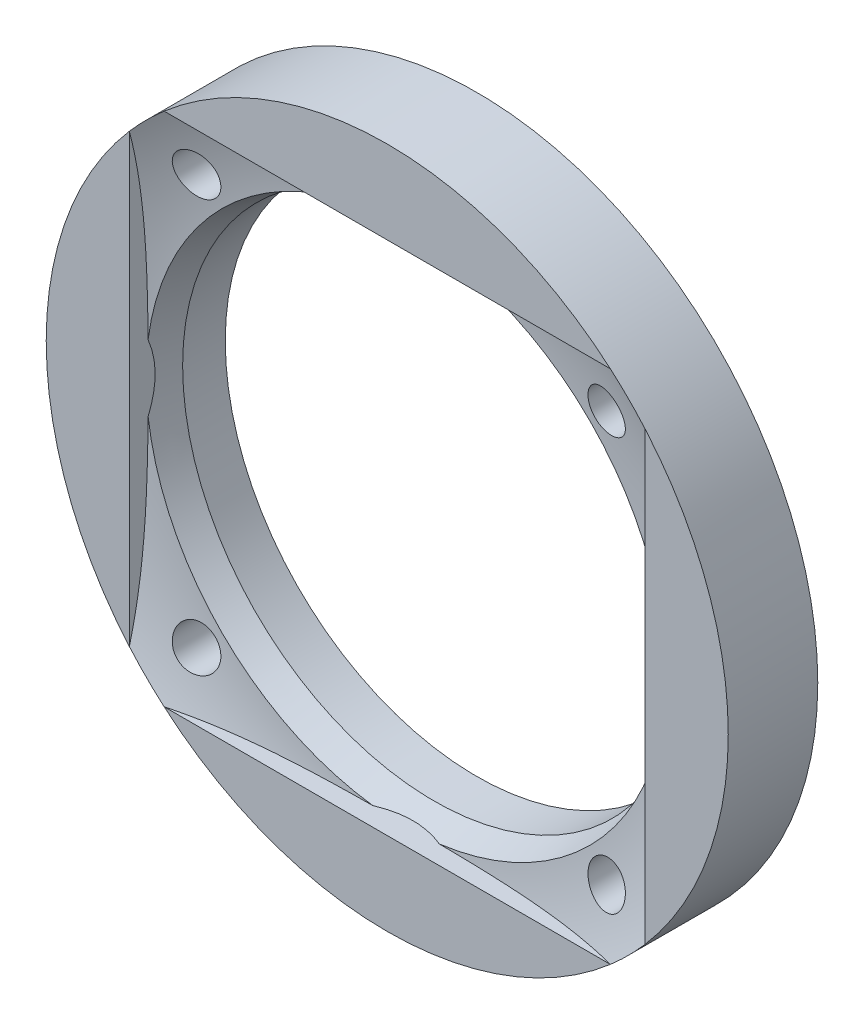
SolidWorks part; units mm, degrees
ref_plane "Front" through (0, 0, 0) normal (0, 0, 1) x (1, 0, 0)
ref_plane "Top" through (0, 0, 0) normal (0, 1, 0) x (1, 0, 0)
ref_plane "Right" through (0, 0, 0) normal (1, 0, 0) x (0, 0, -1)
sketch "Sketch1" plane through (0, 0, 0) normal (0, 1, 0) x (1, 0, 0)
  line L0 (0, 0) -> (0, -40.3584) construction
  line L1 (29.5, 0) -> (40, 0)
  line L2 (29.5, 0) -> (29.5, -5)
  line L3 (40, 0) -> (40, -10.5)
  line L4 (29.5, -5) -> (30.5, -8.3)
  arc A0 (30.5, -8.3) -> (40, -10.5) centre (28.1637, -40) cw
  dimension "D1" = 59
  dimension "D2" = 80
  dimension "D3" = 10.5
  dimension "D4" = 5
  dimension "D5" = 8.3
  dimension "D6" = 61
  dimension "D7" = 40
revolve "Revolve1" add sketch "Sketch1" angle 360 about L0
sketch "Sketch2" plane through (0, 0, 0) normal (0, 0, -1) x (-1, 0, 0)
  line L0 (0, 0) -> (0, 34) construction
  line L1 (24.0416, 24.0416) -> (0, 0) construction
  circle A0 centre (0, 0) radius 34 construction
  circle A1 centre (24.0416, 24.0416) radius 2.5
  circle A2 centre (0, 0) radius 34 construction
  circle A3 centre (24.0416, -24.0416) radius 2.5
  circle A4 centre (0, 0) radius 34 construction
  circle A5 centre (-24.0416, -24.0416) radius 2.5
  circle A6 centre (0, 0) radius 34 construction
  circle A7 centre (-24.0416, 24.0416) radius 2.5
  point P18 (0, 0)
  dimension "D1" = 68
  dimension "D2" = 5
  dimension "D3" = 45
  dimension "D4" = 4
extrude "Cut-Extrude2" cut sketch "Sketch2" against normal through all
sketch "Sketch4" plane through (0, 0, 0) normal (0, 0, -1) x (-1, 0, 0)
  line L1 (-26.1713, 30.25) -> (26.1713, 30.25)
  line L2 (-30.25, 26.1713) -> (-30.25, -26.1713)
  line L3 (-26.1713, -30.25) -> (26.1713, -30.25)
  line L4 (30.25, 26.1713) -> (30.25, -26.1713)
  circle A0 centre (0, 0) radius 40 construction
  arc A1 (-30.25, 26.1713) -> (-30.25, -26.1713) centre (0, 0) ccw
  arc A2 (26.1713, 30.25) -> (-26.1713, 30.25) centre (0, 0) ccw
  arc A3 (30.25, -26.1713) -> (30.25, 26.1713) centre (0, 0) ccw
  arc A4 (-26.1713, -30.25) -> (26.1713, -30.25) centre (0, 0) ccw
  point P0 (0, 0)
  dimension "D1" = 30.25
  dimension "D2" = 30.25
  dimension "D3" = 30.25
  dimension "D4" = 30.25
extrude "Boss-Extrude1" add sketch "Sketch4" against normal blind 10.5
